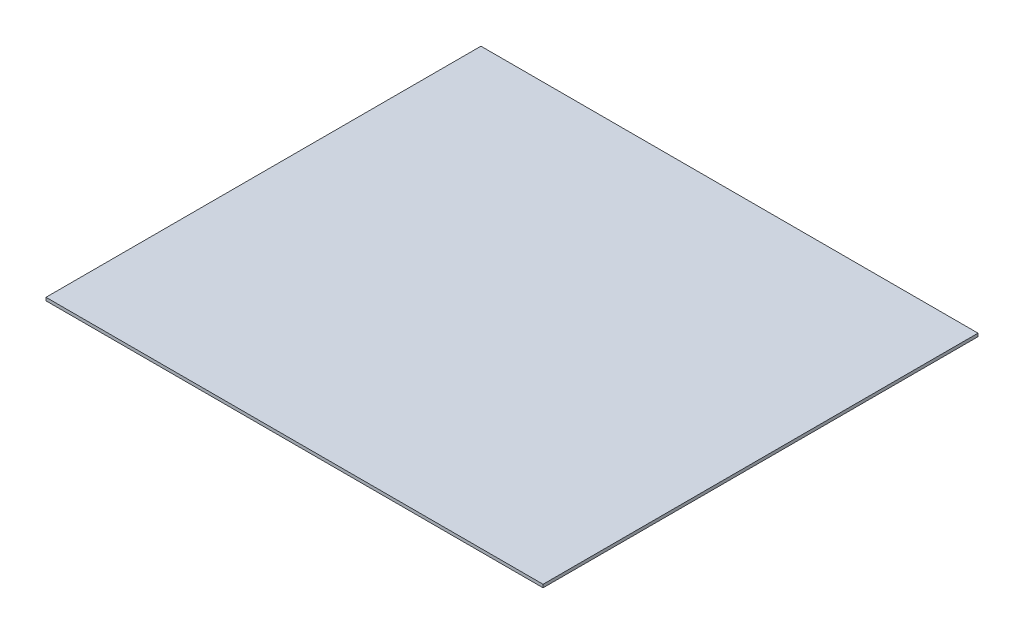
SolidWorks part; units mm, degrees
ref_plane "Front Plane" through (0, 0, 0) normal (0, 0, 1) x (1, 0, 0)
ref_plane "Top Plane" through (0, 0, 0) normal (0, 1, 0) x (1, 0, 0)
ref_plane "Right Plane" through (0, 0, 0) normal (1, 0, 0) x (0, 0, -1)
sketch "Sketch1" plane through (0, 0, 0) normal (0, 1, 0) x (1, 0, 0)
  line L1 (-80, -70) -> (80, -70)
  line L2 (-80, -70) -> (-80, 70)
  line L3 (-80, 70) -> (80, 70)
  line L4 (80, -70) -> (80, 70)
  line L5 (-80, -70) -> (80, 70) construction
  line L6 (-80, 70) -> (80, -70) construction
  point P0 (0, 0)
  dimension "D1" = 160
  dimension "D2" = 140
extrude "Boss-Extrude1" add sketch "Sketch1" along normal blind 1
